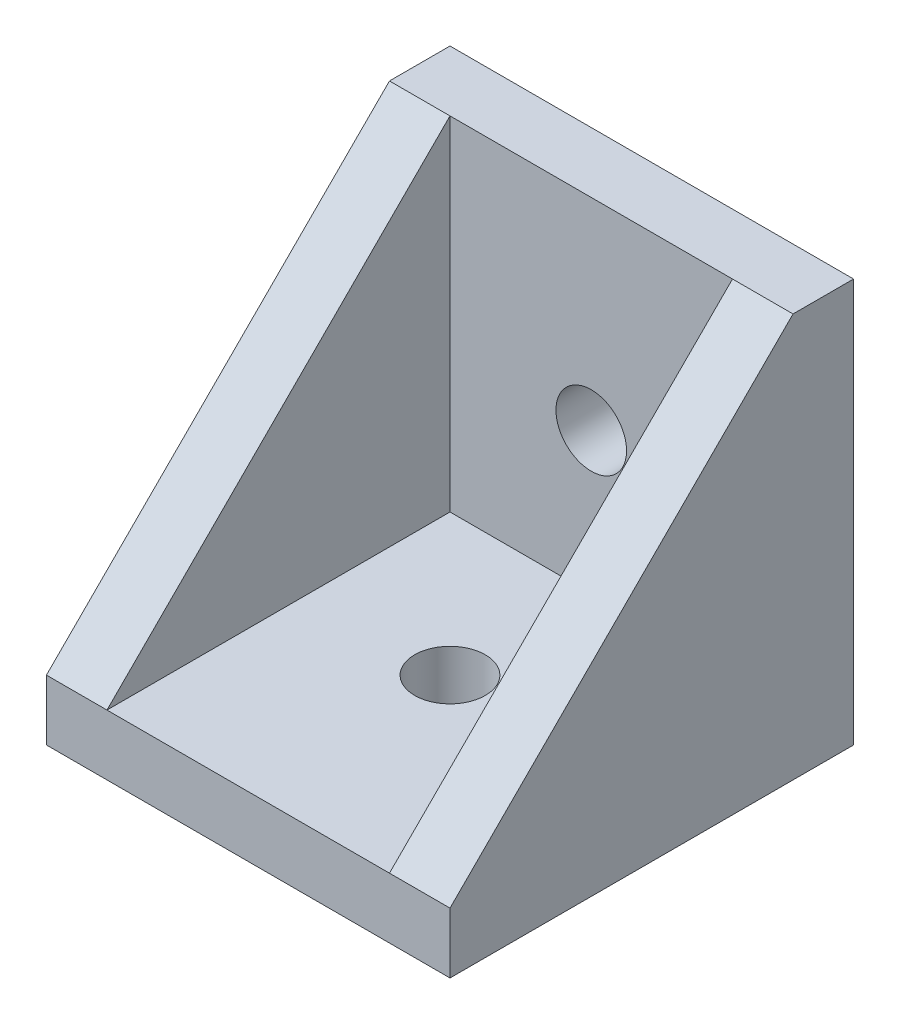
SolidWorks part; units mm, degrees
material "ABS"
ref_plane "Спереди" through (0, 0, 0) normal (0, 0, 1) x (1, 0, 0)
ref_plane "Сверху" through (0, 0, 0) normal (0, 1, 0) x (1, 0, 0)
ref_plane "Справа" through (0, 0, 0) normal (1, 0, 0) x (0, 0, -1)
sketch "Эскиз1" plane through (0, 0, 0) normal (0, 1, 0) x (1, 0, 0)
  line L1 (-10, -10) -> (10, -10)
  line L2 (-10, -10) -> (-10, 10)
  line L3 (-10, 10) -> (10, 10)
  line L4 (10, -10) -> (10, 10)
  line L5 (-10, -10) -> (10, 10) construction
  line L6 (-10, 10) -> (10, -10) construction
  circle A0 centre (0, 0) radius 1.75
  point P0 (0, 0)
extrude "Бобышка-Вытянуть1" add sketch "Эскиз1" along normal blind 3
sketch "Эскиз2" plane through (0, 3, 0) normal (0, 1, 0) x (1, 0, 0)
  line L0 (10, -10) -> (10, 10) construction
  line L1 (-10, 10) -> (10, 10)
  line L2 (-10, 10) -> (-10, 7)
  line L3 (-10, 7) -> (10, 7)
  line L4 (10, 10) -> (10, 7)
extrude "Бобышка-Вытянуть2" add sketch "Эскиз2" along normal blind 17
sketch "Эскиз3" plane through (0, 0, -7) normal (0, 0, 1) x (1, 0, 0)
  line L1 (-10, 0) -> (0, 0)
  line L2 (-10, 0) -> (-10, 10)
  line L3 (-10, 10) -> (-1.75, 10)
  line L4 (0, 0) -> (0, 8.25)
  circle A0 centre (0, 10) radius 1.75
extrude "Вырез-Вытянуть1" cut sketch "Эскиз3" against normal blind 17 contours A0
sketch "Эскиз4" plane through (-10, 0, 0) normal (-1, 0, 0) x (0, 0, 1)
  line L0 (-7, 20) -> (10, 3)
  line L1 (10, 3) -> (-7, 3)
  line L2 (-7, 3) -> (-7, 20)
extrude "Бобышка-Вытянуть4" add sketch "Эскиз4" against normal blind 3
sketch "Эскиз5" plane through (10, 0, 0) normal (1, 0, 0) x (0, 0, -1)
  line L0 (7, 20) -> (7, 3)
  line L1 (7, 3) -> (-10, 3)
  line L2 (-10, 3) -> (7, 20)
extrude "Бобышка-Вытянуть5" add sketch "Эскиз5" against normal blind 3
